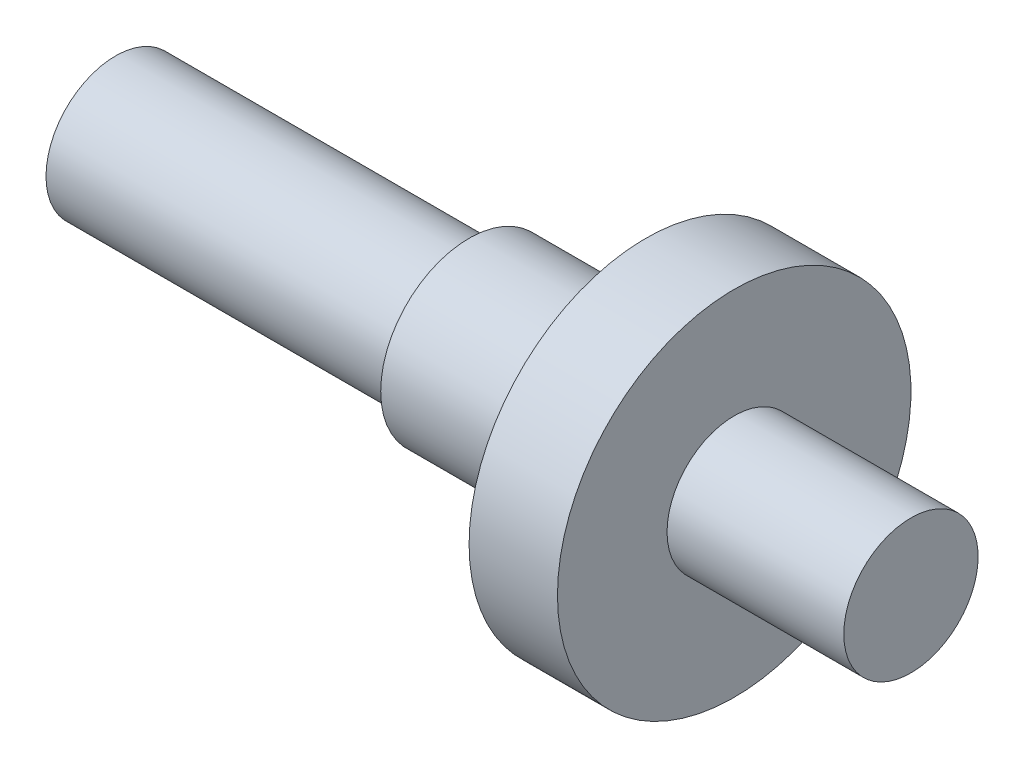
SolidWorks part; units mm, degrees
material "ALUMINUM 6061"
ref_plane "Front Plane" through (0, 0, 0) normal (0, 0, 1) x (1, 0, 0)
ref_plane "Top Plane" through (0, 0, 0) normal (0, 1, 0) x (1, 0, 0)
ref_plane "Right Plane" through (0, 0, 0) normal (1, 0, 0) x (0, 0, -1)
sketch "Sketch1" plane through (0, 0, 0) normal (0, 0, 1) x (1, 0, 0)
  line L0 (0, 0) -> (9.525, 0)
  line L1 (9.525, 0) -> (9.525, 2.413)
  line L2 (9.525, 2.413) -> (3.175, 2.413)
  line L3 (3.175, 2.413) -> (3.175, 6.35)
  line L4 (3.175, 6.35) -> (0, 6.35)
  line L5 (0, 6.35) -> (0, 3.175)
  line L6 (0, 3.175) -> (-6.35, 3.175)
  line L7 (-19.05, 2.5) -> (-19.05, 0)
  line L8 (-19.05, 0) -> (0, 0)
  line L9 (0, 0) -> (0, 3.175) construction
  line L10 (0, 0) -> (0, -3.175) construction
  line L11 (3.175, 2.413) -> (3.175, 0) construction
  line L12 (3.175, 0) -> (3.175, -2.413) construction
  line L13 (-6.35, 3.175) -> (-6.35, 2.5)
  line L14 (-6.35, 2.5) -> (-19.05, 2.5)
  line L15 (-6.35, 2.5) -> (-6.35, 0) construction
  line L16 (-6.35, 0) -> (-6.35, -2.5) construction
  dimension "D1" = 6.35
  dimension "D2" = 19.05
  dimension "D3" = 3.175
  dimension "D4" = 6.35
  dimension "D5" = 6.35
  dimension "D6" = 4.826
  dimension "D7" = 6.35
  dimension "D8" = 5
revolve "Revolve1" add sketch "Sketch1" angle 360 about L8
cosmetic thread "Cosmetic Thread1" parameters "D2"=3.8811
move or copy body "Body-Move/Copy1" [suppressed] bodies to move or copy 101
